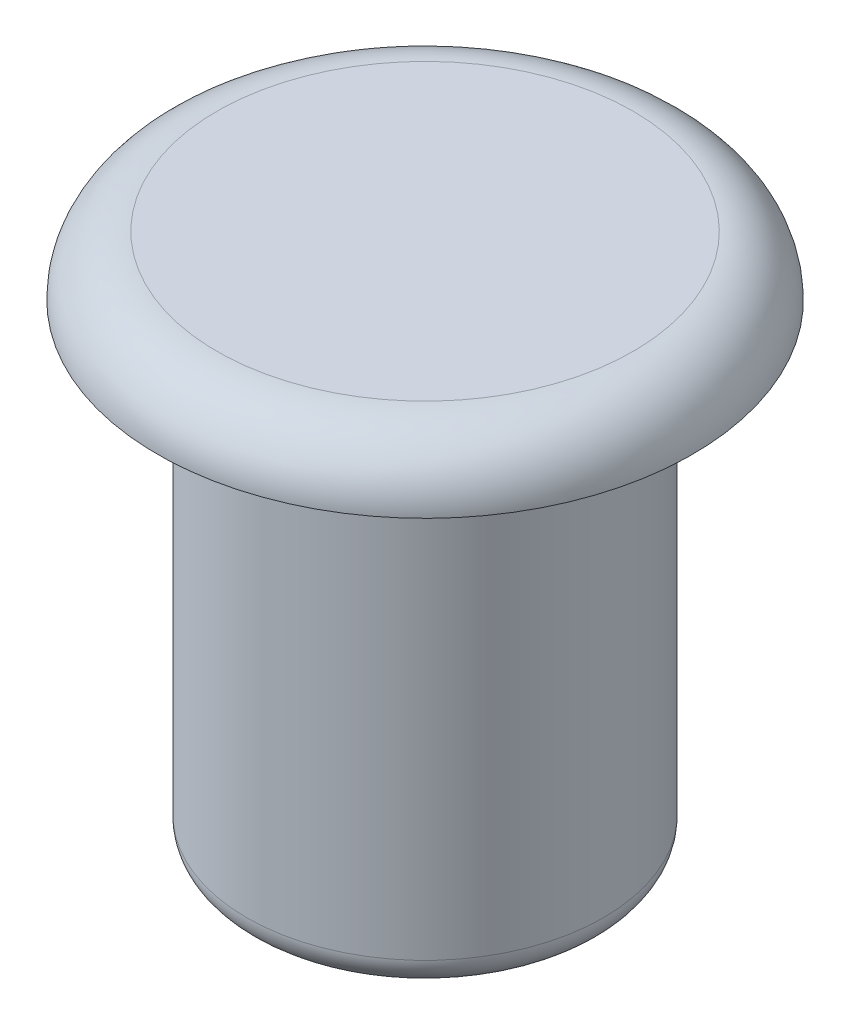
SolidWorks part; units mm, degrees
material "ASTM A36"
ref_plane "Plano frontal" through (0, 0, 0) normal (0, 0, 1) x (1, 0, 0)
ref_plane "Plano superior" through (0, 0, 0) normal (0, 1, 0) x (1, 0, 0)
ref_plane "Plano direito" through (0, 0, 0) normal (1, 0, 0) x (0, 0, -1)
sketch "Esboço1" plane through (0, 0, 0) normal (1, 0, 0) x (0, 0, -1)
  line L0 (0, 0) -> (0, 4573.8968) construction
  line L1 (0, 9) -> (-3.5, 9)
  line L2 (-4.5, 8) -> (-3, 8)
  line L3 (-3, 8) -> (-3, 0.5)
  line L4 (-2.5, 0) -> (0, 0)
  line L5 (0, 0) -> (0, 9)
  arc A0 (-3.5, 9) -> (-4.5, 8) centre (-3.5, 8) ccw
  arc A1 (-3, 0.5) -> (-2.5, 0) centre (-2.5, 0.5) ccw
  dimension "D5" = 0.5
  dimension "D1" = 9
  dimension "D2" = 6
  dimension "D3" = 9
  dimension "D4" = 1
revolve "Revolução1" add sketch "Esboço1" angle 360 about L0
